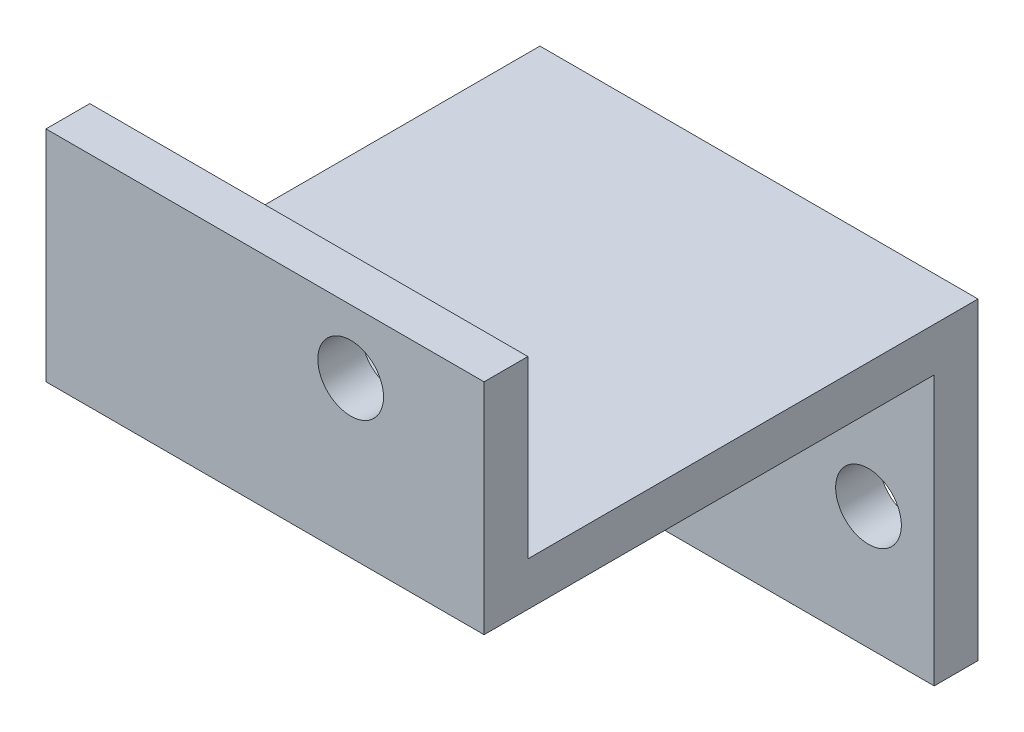
SolidWorks part; units mm, degrees
ref_plane "Front" through (0, 0, 0) normal (0, 0, 1) x (1, 0, 0)
ref_plane "Top" through (0, 0, 0) normal (0, 1, 0) x (1, 0, 0)
ref_plane "Right" through (0, 0, 0) normal (1, 0, 0) x (0, 0, -1)
sketch "Esquisse1" plane through (0, 0, 0) normal (0, 0, 1) x (1, 0, 0)
  line L1 (0, 0) -> (20, 0)
  line L2 (0, 0) -> (0, 14.3)
  line L3 (0, 14.3) -> (20, 14.3)
  line L4 (20, 0) -> (20, 14.3)
  dimension "D1" = 20
  dimension "D2" = 14.3
extrude "Boss.-Extru.1" add sketch "Esquisse1" along normal blind 2
sketch "Esquisse2" plane through (0, 0, 2) normal (0, 0, 1) x (1, 0, 0)
  line L0 (20, 0) -> (20, 14.3) construction
  line L1 (0, 14.3) -> (20, 14.3)
  line L2 (0, 14.3) -> (0, 12.3)
  line L3 (0, 12.3) -> (20, 12.3)
  line L4 (20, 14.3) -> (20, 12.3)
  dimension "D1" = 2
extrude "Boss.-Extru.2" add sketch "Esquisse2" along normal blind 20.55
sketch "Esquisse3" plane through (0, 14.3, 0) normal (0, 1, 0) x (1, 0, 0)
  line L0 (0, -22.55) -> (0, 0) construction
  line L1 (20, -22.55) -> (0, -22.55)
  line L2 (20, -22.55) -> (20, -20.55)
  line L3 (20, -20.55) -> (0, -20.55)
  line L4 (0, -22.55) -> (0, -20.55)
  dimension "D1" = 2
extrude "Boss.-Extru.3" add sketch "Esquisse3" along normal blind 8
sketch "Esquisse4" plane through (0, 0, 0) normal (0, 0, -1) x (-1, 0, 0)
  line L0 (-20, 0) -> (-20, 14.3) construction
  line L1 (0, 14.3) -> (0, 0) construction
  line L3 (0, 0) -> (-20, 0) construction
  circle A0 centre (-17, 5.6) radius 1.5
  circle A1 centre (-3, 5.6) radius 1.5
  dimension "D1" = 3
  dimension "D2" = 3
  dimension "D3" = 3
  dimension "D4" = 3
  dimension "D5" = 5.6
  dimension "D6" = 5.6
extrude "Enlèv. mat.-Extru.2" cut sketch "Esquisse4" against normal blind 8
sketch "Esquisse5" plane through (0, 0, 22.55) normal (0, 0, 1) x (1, 0, 0)
  line L1 (0, 22.3) -> (20, 22.3) construction
  line L3 (20, 12.3) -> (20, 22.3) construction
  circle A0 centre (13.91, 19.4) radius 1.5
  dimension "D1" = 3
  dimension "D2" = 2.9
  dimension "D3" = 6.09
extrude "Enlèv. mat.-Extru.3" cut sketch "Esquisse5" against normal blind 8
